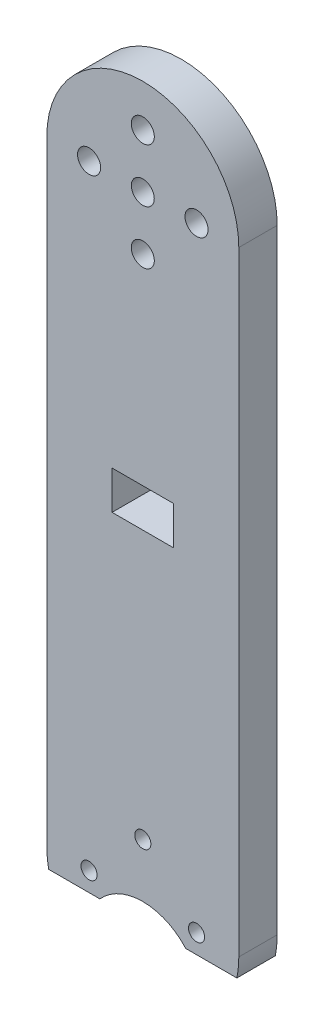
SolidWorks part; units mm, degrees
ref_plane "Front Plane" through (0, 0, 0) normal (0, 0, 1) x (1, 0, 0)
ref_plane "Top Plane" through (0, 0, 0) normal (0, 1, 0) x (1, 0, 0)
ref_plane "Right Plane" through (0, 0, 0) normal (1, 0, 0) x (0, 0, -1)
sketch "Sketch1" plane through (0, 0, 0) normal (0, 0, 1) x (1, 0, 0)
  line L0 (-4, -80) -> (-6, -80) construction
  line L1 (0, -76) -> (0, -74) construction
  line L4 (-12.5, 0) -> (-12.5, -80)
  line L5 (12.5, 0) -> (12.5, -80)
  line L6 (-6, -80) -> (-7, -80) construction
  line L7 (0, -74) -> (0, -73) construction
  line L8 (4, -80) -> (6, -80) construction
  line L9 (6, -80) -> (7, -80) construction
  line L10 (0, 5.4939) -> (0, 1.4939) construction
  line L11 (0, -92.5) -> (0, -82.5) construction
  line L12 (0, -82.5) -> (-12.2474, -82.5) construction
  circle A2 centre (0, 6.9939) radius 1.5
  circle A6 centre (0, 0) radius 1.4939
  circle A20 centre (-7, -80) radius 1.05
  circle A21 centre (0, -73) radius 1.05
  circle A22 centre (7, -80) radius 1.05
  circle A23 centre (-6.9939, 0) radius 1.5
  circle A24 centre (0, -6.9939) radius 1.5
  circle A25 centre (6.9939, 0) radius 1.5
  arc A26 (12.5, 0) -> (-12.5, 0) centre (0, 0) ccw
  arc A27 (-12.5, -80) -> (12.5, -80) centre (0, -80) ccw
  point P6 (0, 12.5)
  point P7 (0, -92.5)
  point P24 (0, 0)
  dimension "D2" = 105
  dimension "D3" = 3
  dimension "D4" = 4
  dimension "D5" = 25
  dimension "D6" = 25
  dimension "D7" = 4
  dimension "D10" = 12.2474
  dimension "D12" = 2
  dimension "D13" = 2
  dimension "D14" = 1
  dimension "D15" = 1
  dimension "D16" = 1
  dimension "D17" = 2.1
  dimension "D18" = 2.1
  dimension "D19" = 2.1
  dimension "D8" = 2
  dimension "D9" = 10
extrude "Boss-Extrude1" add sketch "Sketch1" along normal blind 5
sketch "Sketch3" plane through (0, 0, 5) normal (0, 0, 1) x (1, 0, 0)
  line L1 (-4, -33.1139) -> (4, -33.1139)
  line L2 (-4, -33.1139) -> (-4, -38.1139)
  line L3 (0, -8.4939) -> (0, -35.6139) construction
  line L4 (-4, -38.1139) -> (4, -38.1139)
  line L6 (4, -33.1139) -> (4, -38.1139)
  line L7 (-4, -33.1139) -> (4, -38.1139) construction
  line L8 (-4, -38.1139) -> (4, -33.1139) construction
  circle A0 centre (0, -6.9939) radius 1.5 construction
  dimension "D1" = 27.12
  dimension "D2" = 8
  dimension "D3" = 5
extrude "Cut-Extrude3" cut sketch "Sketch3" against normal blind 10
sketch "Sketch5" plane through (0, 0, 5) normal (0, 0, 1) x (1, 0, 0)
  line L0 (0, -92.5) -> (0, -82.5) construction
  line L1 (-12.2474, -82.5) -> (12.2474, -82.5)
  line L2 (0, -80) -> (0, -82.5) construction
  line L3 (-12.2474, -82.5) -> (-12.2474, -92.5)
  line L4 (-12.2474, -92.5) -> (12.2474, -92.5)
  line L5 (12.2474, -92.5) -> (12.2474, -82.5)
  arc A0 (-12.5, -80) -> (12.5, -80) centre (0, -80) ccw construction
  circle A1 centre (0, -87.5) radius 7.5
  arc M13 (-12.5, -80) -> (12.5, -80) centre (0, -80) ccw
  dimension "D2" = 15
  dimension "D1" = 10
  dimension "D3" = 10
extrude "Cut-Extrude4" cut sketch "Sketch5" against normal blind 10 contours L1 A1 M13 | L1 A1 | A1 M13
